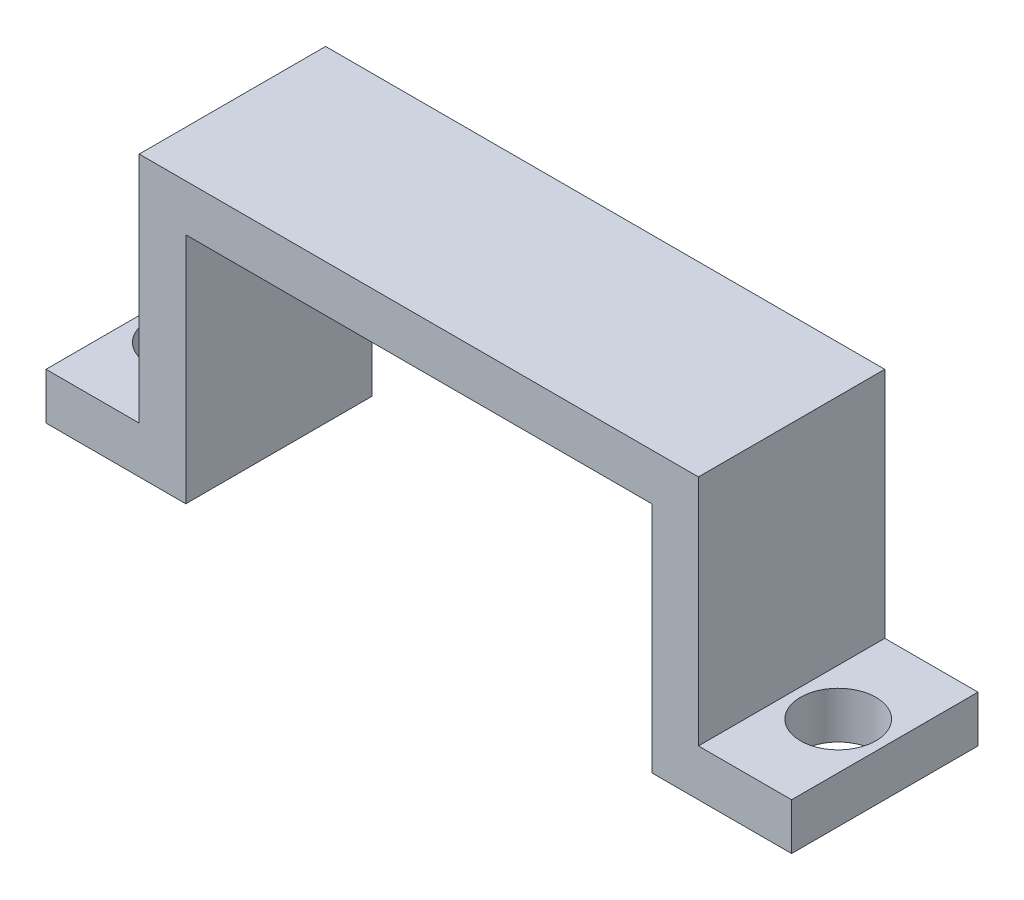
SolidWorks part; units mm, degrees
ref_plane "Front Plane" through (0, 0, 0) normal (0, 0, 1) x (1, 0, 0)
ref_plane "Top Plane" through (0, 0, 0) normal (0, 1, 0) x (1, 0, 0)
ref_plane "Right Plane" through (0, 0, 0) normal (1, 0, 0) x (0, 0, -1)
sketch "Sketch1" plane through (0, 0, 0) normal (0, 1, 0) x (1, 0, 0)
  line L1 (0, 0) -> (60, 0)
  line L2 (0, 0) -> (0, 20)
  line L3 (0, 20) -> (60, 20)
  line L4 (60, 0) -> (60, 20)
  dimension "D1" = 20
  dimension "D2" = 60
extrude "Boss-Extrude1" add sketch "Sketch1" along normal blind 5
sketch "Sketch2" plane through (0, 0, 0) normal (0, -1, 0) x (1, 0, 0)
  line L0 (60, -20) -> (0, -20) construction
  line L1 (0, 0) -> (5, 0)
  line L2 (0, 0) -> (0, -20)
  line L3 (0, -20) -> (5, -20)
  line L4 (5, 0) -> (5, -20)
  line L6 (60, 0) -> (55, 0)
  line L7 (60, 0) -> (60, -20)
  line L8 (60, -20) -> (55, -20)
  line L9 (55, 0) -> (55, -20)
  dimension "D1" = 5
  dimension "D2" = 5
extrude "Boss-Extrude2" add sketch "Sketch2" along normal blind 25
sketch "Sketch3" plane through (60, 0, 0) normal (1, 0, 0) x (0, 0, -1)
  line L0 (0, -25) -> (20, -25)
  line L1 (0, -25) -> (0, -20)
  line L2 (20, -25) -> (20, -20)
  line L3 (0, -20) -> (20, -20)
  dimension "D1" = 5
extrude "Boss-Extrude3" add sketch "Sketch3" along normal blind 10
sketch "Sketch4" plane through (0, 0, 0) normal (-1, 0, 0) x (0, 0, 1)
  line L0 (-20, -25) -> (0, -25)
  line L1 (-20, -25) -> (-20, -20)
  line L2 (0, -25) -> (0, -20)
  line L3 (-20, -20) -> (0, -20)
  line L4 (0, -25) -> (-20, -25) construction
  dimension "D1" = 5
extrude "Boss-Extrude4" add sketch "Sketch4" along normal blind 10
sketch "Sketch5" plane through (0, -20, 0) normal (0, 1, 0) x (1, 0, 0)
  line L0 (70, 10) -> (60, 10)
  line L1 (70, 20) -> (70, 0) construction
  line L2 (60, 0) -> (60, 20) construction
  line L3 (0, 10) -> (-10, 10)
  line L4 (0, 0) -> (0, 20) construction
  line L5 (-10, 0) -> (-10, 20) construction
  circle A0 centre (65, 10) radius 4.05
  circle A1 centre (-5, 10) radius 4.05
  dimension "D1" = 8.1
  dimension "D2" = 8.1
extrude "Cut-Extrude1" cut sketch "Sketch5" against normal blind 20 contours L0 A0 | A1
